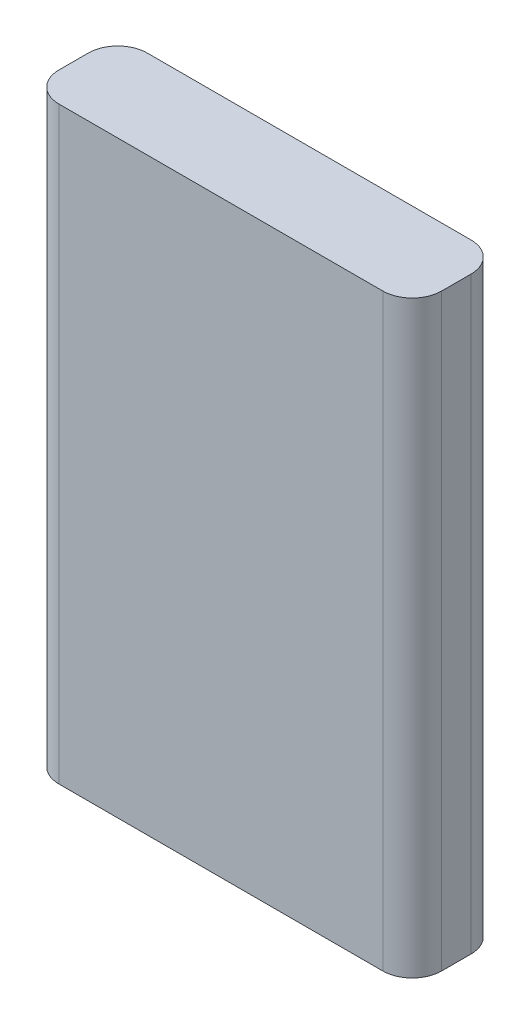
SolidWorks part; units mm, degrees
ref_plane "Alzado" through (0, 0, 0) normal (0, 0, 1) x (1, 0, 0)
ref_plane "Planta" through (0, 0, 0) normal (0, 1, 0) x (1, 0, 0)
ref_plane "Vista lateral" through (0, 0, 0) normal (1, 0, 0) x (0, 0, -1)
sketch "Croquis1" plane through (0, 0, 0) normal (0, 0, 1) x (1, 0, 0)
  line L1 (-19.645, 9.8225) -> (-6.645, 9.8225)
  line L2 (-19.645, 9.8225) -> (-19.645, -10.1775)
  line L3 (-19.645, -10.1775) -> (-6.645, -10.1775)
  line L4 (-6.645, 9.8225) -> (-6.645, -10.1775)
  dimension "D1" = 20
  dimension "D2" = 13
extrude "Saliente-Extruir1" add sketch "Croquis1" along normal blind 3
fillet "Redondeo1" radius 1 4 edges at (-6.645, -0.1775, 0) (-6.645, -0.1775, 3) (-19.645, -0.1775, 0) (-19.645, -0.1775, 3)
